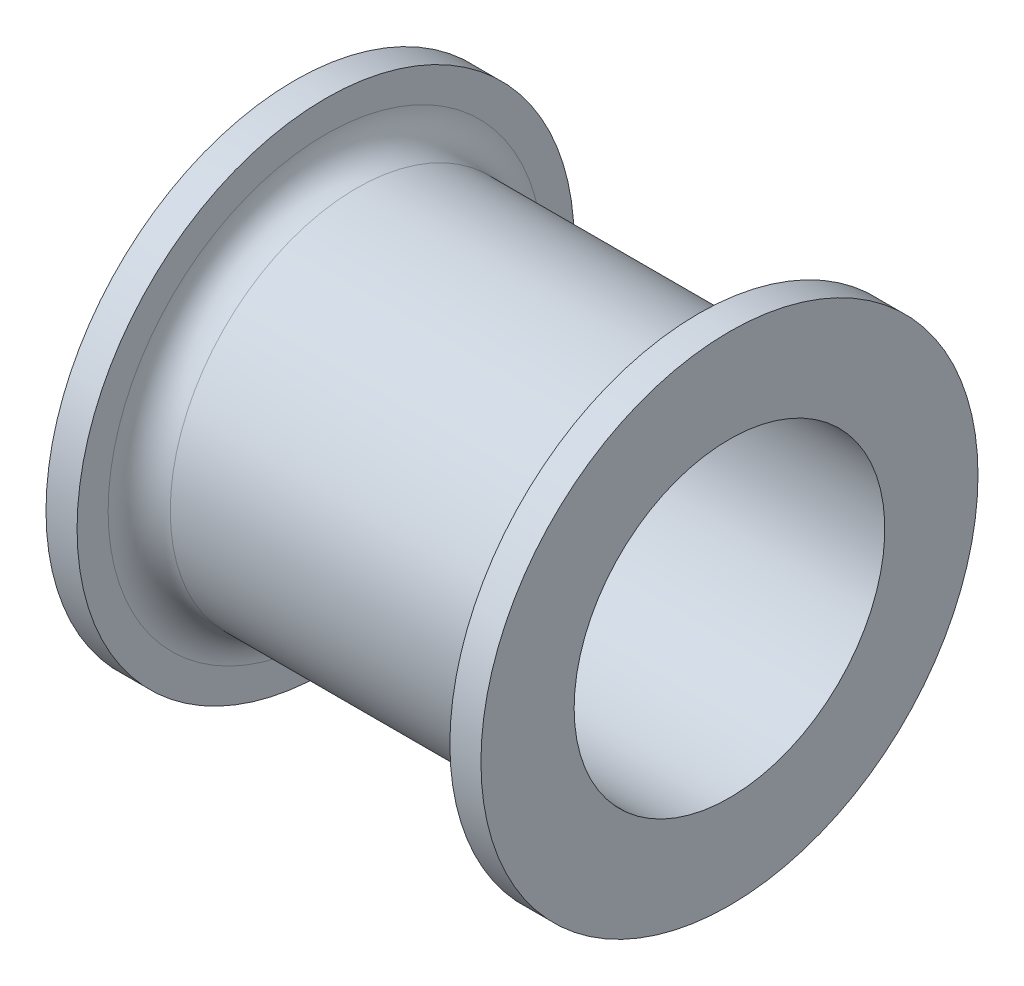
SolidWorks part; units mm, degrees
ref_plane "Front Plane" through (0, 0, 0) normal (0, 0, 1) x (1, 0, 0)
ref_plane "Top Plane" through (0, 0, 0) normal (0, 1, 0) x (1, 0, 0)
ref_plane "Right Plane" through (0, 0, 0) normal (1, 0, 0) x (0, 0, -1)
sketch "Sketch1" plane through (0, 0, 0) normal (0, 1, 0) x (1, 0, 0)
  line L0 (0, 8) -> (0, 5)
  line L1 (0, 5) -> (14, 5)
  line L2 (14, 5) -> (14, 8)
  line L3 (14, 8) -> (13, 8)
  line L4 (13, 8) -> (13, 6)
  line L5 (13, 6) -> (1, 6)
  line L6 (1, 6) -> (1, 8)
  line L7 (1, 8) -> (0, 8)
  line L8 (0, 0) -> (2.1647, 0) construction
  dimension "D1" = 1
  dimension "D2" = 1
  dimension "D3" = 1
  dimension "D4" = 3
  dimension "D5" = 3
  dimension "D6" = 5
  dimension "D7" = 14
revolve "Revolve1" add sketch "Sketch1" angle 360 about L8
fillet "Fillet1" radius 1 2 edges at (13, 0, 6) (1, 0, 6)
